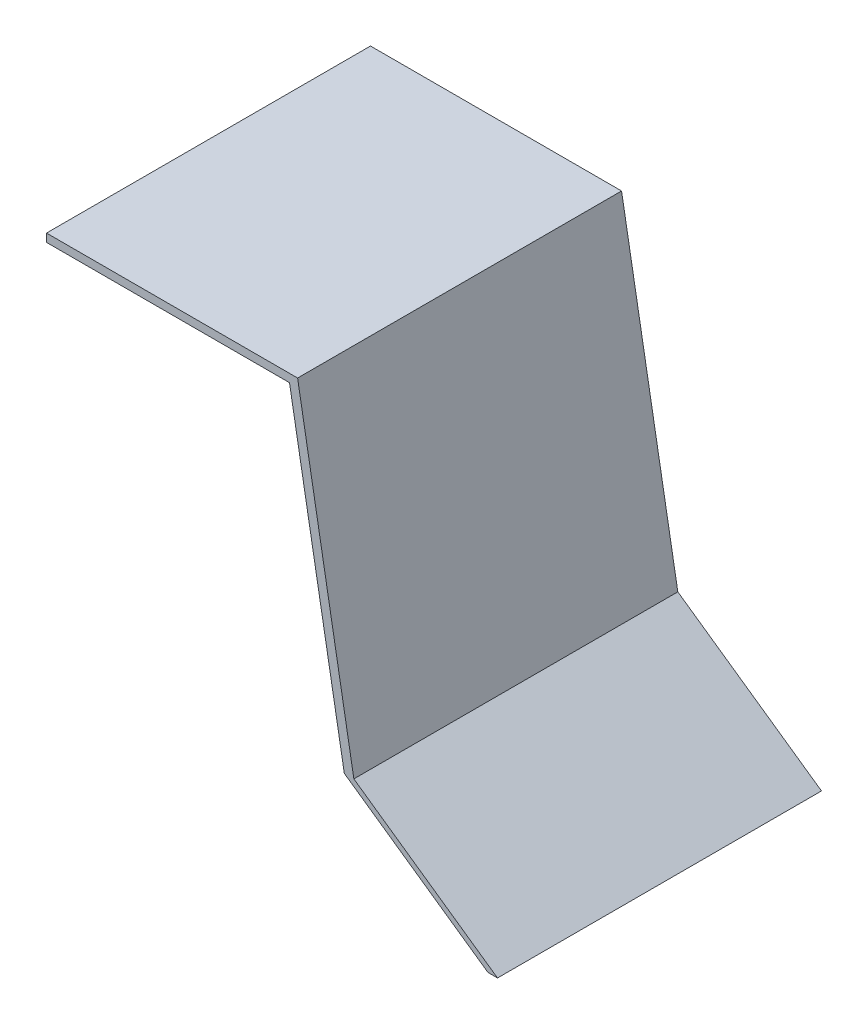
SolidWorks part; units mm, degrees
ref_plane "Front Plane" through (0, 0, 0) normal (0, 0, 1) x (1, 0, 0)
ref_plane "Top Plane" through (0, 0, 0) normal (0, 1, 0) x (1, 0, 0)
ref_plane "Right Plane" through (0, 0, 0) normal (1, 0, 0) x (0, 0, -1)
sketch "Sketch1" plane through (0, 0, 0) normal (0, 1, 0) x (1, 0, 0)
  line L1 (127, 0) -> (508, 0)
  line L2 (127, 0) -> (127, 508)
  line L3 (127, 508) -> (508, 508)
  line L4 (508, 0) -> (508, 508)
  point P5 (69.6108, 0)
  point P7 (507.8869, 10.7184)
  dimension "D1" = 508
  dimension "D2" = 508
  dimension "D3" = 127
extrude "Boss-Extrude1" add sketch "Sketch1" along normal blind 12.7 contours L2 L3 L4 L1
ref_plane "Plane1" through (317.5, 0, 0) normal (1, 0, 0) x (0, 0, -1)
sketch "Sketch3" plane through (317.5, 0, 0) normal (1, 0, 0) x (0, 0, -1)
  line L0 (228.6, 0) -> (228.6, -63.5)
  line L1 (0, 0) -> (508, 0) construction
  line L2 (279.4, 0) -> (279.4, -63.5)
  line L3 (228.6, 0) -> (279.4, 0)
  arc A0 (228.6, -63.5) -> (279.4, -63.5) centre (254, -63.5) ccw
  circle A1 centre (254, -63.5) radius 6.35
  point P6 (254, 0)
  dimension "D3" = 63.5
  dimension "D4" = 12.7
  dimension "D1" = 25.4
  dimension "D2" = 25.4
extrude "Boss-Extrude2" add sketch "Sketch3" along normal mid plane 25.4
sketch "Sketch6" plane through (0, 0, 0) normal (0, 0, 1) x (1, 0, 0)
  line L0 (520.7, 12.7) -> (608.9133, -487.5823)
  line L2 (593.9739, -487.5823) -> (508, 0)
  line L4 (127, 0) -> (508, 0) construction
  line L5 (508, 0) -> (508, 12.7)
  line L6 (508, 12.7) -> (520.7, 12.7)
  line L7 (608.9133, -487.5823) -> (834.1808, -645.3163)
  line L8 (834.1808, -645.3163) -> (819.2414, -645.3163)
  line L9 (819.2414, -645.3163) -> (593.9739, -487.5823)
  point P3 (848.099, -646.0259)
  point P9 (0, 0)
  point P10 (695.7347, -608.1011)
  point P11 (593.9739, -645.3163)
  point P14 (768.4019, -641.7779)
  point P15 (834.9977, -643.5728)
  point P16 (835.9816, -646.5773)
  dimension "D1" = 508
  dimension "D2" = 100
  dimension "D3" = 12.7
  dimension "D4" = 35
  dimension "D5" = 157.734
extrude "Boss-Extrude4" add sketch "Sketch6" against normal up to surface (508 mm away) up to face at (317.5, 6.35, -508)
